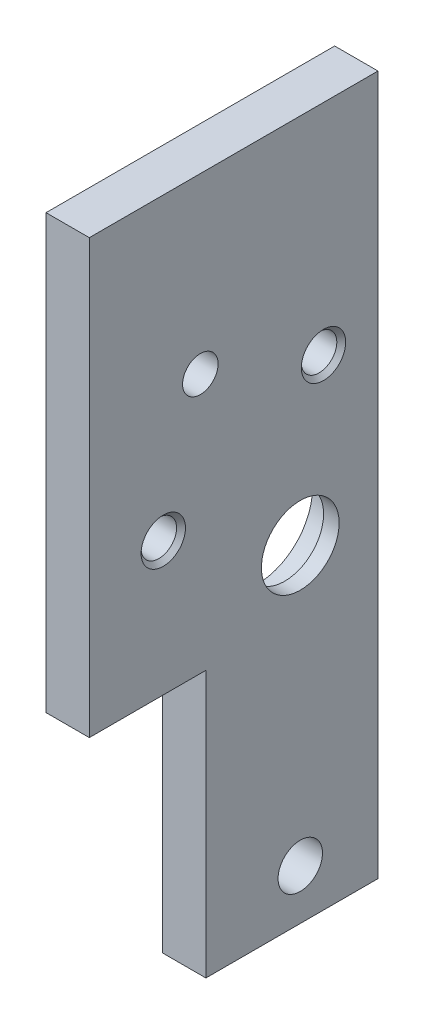
SolidWorks part; units mm, degrees
ref_plane "Front Plane" through (0, 0, 0) normal (0, 0, 1) x (1, 0, 0)
ref_plane "Top Plane" through (0, 0, 0) normal (0, 1, 0) x (1, 0, 0)
ref_plane "Right Plane" through (0, 0, 0) normal (1, 0, 0) x (0, 0, -1)
sketch "Sketch1" plane through (0, 0, 0) normal (1, 0, 0) x (0, 0, -1)
  line L1 (0, 0) -> (-30, 0)
  line L2 (0, 0) -> (0, 63)
  line L3 (0, 63) -> (-30, 63)
  line L4 (-30, 0) -> (-30, 63)
  dimension "D1" = 30
  dimension "D2" = 63
extrude "Boss-Extrude1" add sketch "Sketch1" against normal blind 3.9
sketch "Sketch2" plane through (0, 0, 0) normal (1, 0, 0) x (0, 0, -1)
  line L0 (-30, 0) -> (0, 0) construction
  line L1 (0, 0) -> (0, 63) construction
  circle A0 centre (-7, 29.5) radius 5
  dimension "D1" = 10
  dimension "D2" = 29.5
  dimension "D3" = 7
extrude "Cut-Extrude1" cut sketch "Sketch2" against normal through all
sketch "Sketch4" plane through (0, 0, 0) normal (1, 0, 0) x (0, 0, -1)
  line L0 (0, 0) -> (0, 63) construction
  line L1 (-15.3544, 41.2) -> (-2.5009, 48.379)
  line L2 (-2.5009, 48.379) -> (-15.1448, 55.921)
  line L3 (-15.1448, 55.921) -> (-15.3544, 41.2)
  circle A0 centre (-11, 48.5) radius 4.25 construction
  circle A1 centre (-7, 29.5) radius 5 construction
  dimension "D2" = 19
  dimension "D1" = 8.5
  dimension "D3" = 11
  dimension "D4" = 8.4991
hole_wizard "M4x0.7 Tapped Hole1" [suppressed] positions "3DSketch2" profile "Sketch6" tap size "M4x0.7" standard "ANSI Metric"
sketch3d "3DSketch2"
  point P0 (0, 38.7, 15.3544)
  point P3 (0, 45.879, 2.5009)
  point P6 (0, 53.421, 15.1448)
sketch "Sketch6" plane through (0, 38.7, 15.3544) normal (0, 1, 0) x (0, 0, -1)
  line L0 (0, 0) -> (0, 4)
  line L1 (0, 4) -> (1.05, 4)
  line L3 (1.05, 4) -> (1.05, 2)
  line L4 (1.05, 2) -> (1.65, 2)
  line L5 (1.65, 2) -> (1.65, 0)
  line L7 (1.65, 0) -> (0, 0)
  line L11 (0, -6.35) -> (0, 107.95) construction
  dimension "Thru Tap Drill Dia." = 2.1
  dimension "Thru Tap Drill Depth" = 4
  dimension "Thread Major Dia." = 3.3
  dimension "Thread Depth" = 2
sketch "Sketch7" [suppressed] plane through (-4, 0, 0) normal (-1, 0, 0) x (0, 0, 1)
  line L1 (15.3544, 38.7) -> (15.1448, 53.421)
  line L2 (15.1448, 53.421) -> (2.5009, 45.879)
  line L3 (2.5009, 45.879) -> (15.3544, 38.7)
  circle A0 centre (11, 46) radius 4.25 construction
hole_wizard "CBORE for M3 Pan Head Machine Screw1" [suppressed] positions "3DSketch3" profile "Sketch8" counterbore size "M3" standard "ANSI Metric"
sketch3d "3DSketch3" [suppressed]
  point P0 (-4, 46, 11)
sketch "Sketch8" [suppressed] plane through (-4, 46, 11) normal (0, 1, 0) x (0, 0, 1)
  line L0 (0, 0) -> (0, 4)
  line L1 (0, 4) -> (1.6, 4)
  line L3 (1.6, 4) -> (1.6, 1)
  line L4 (1.6, 1) -> (5.1, 1)
  line L5 (5.1, 1) -> (5.1, 0)
  line L7 (5.1, 0) -> (0, 0)
  line L11 (0, -6.35) -> (0, 107.95) construction
  dimension "Thru Hole Dia." = 3.2
  dimension "Thru Hole Depth" = 4
  dimension "C'Bore Dia." = 10.2
  dimension "C'Bore Depth" = 1
sketch "Sketch10" plane through (0, 0, 0) normal (1, 0, 0) x (0, 0, -1)
  line L0 (0, 0) -> (0, 63) construction
  line L1 (-30, 0) -> (0, 0) construction
  circle A0 centre (-7, 4.5) radius 2
  dimension "D1" = 4
  dimension "D2" = 7
  dimension "D3" = 4.5
hole_wizard "Ø4.0 (4) Diameter Hole1" positions "3DSketch4" profile "Sketch11" hole size "Ø4.0" standard "ANSI Metric" end condition through all
sketch3d "3DSketch4"
  point P0 (0, 4.5, 7)
sketch "Sketch11" plane through (0, 4.5, 7) normal (0, 1, 0) x (0, 0, -1)
  line L0 (0, 0) -> (0, 3.9)
  line L1 (0, 3.9) -> (2, 3.9)
  line L2 (2, 3.9) -> (2, 0)
  line L5 (2, 0) -> (0, 0)
  line L11 (0, -6.35) -> (0, 107.95) construction
  dimension "Thru Hole Dia." = 4
  dimension "Thru Hole Depth" = 3.9
sketch "Sketch12" plane through (0, 0, 0) normal (1, 0, 0) x (0, 0, -1)
  line L1 (-30, 0) -> (-15.5, 0)
  line L2 (-30, 0) -> (-30, 24)
  line L3 (-30, 24) -> (-15.5, 24)
  line L4 (-15.5, 0) -> (-15.5, 24)
  dimension "D1" = 14.5
  dimension "D2" = 24
extrude "Cut-Extrude2" cut sketch "Sketch12" against normal through all
sketch "Sketch13" plane through (-3.9, 0, 0) normal (-1, 0, 0) x (0, 0, 1)
  line L0 (0, 0) -> (0, 63) construction
  circle A0 centre (16, 47.3606) radius 1.5
  circle A1 centre (7, 29.5) radius 5 construction
  dimension "D1" = 3
  dimension "D2" = 20
  dimension "D3" = 16
hole_wizard "CBORE for M3 Pan Head Machine Screw2" positions "3DSketch5" profile "Sketch14" counterbore size "M3" standard "ANSI Metric" end condition through all
sketch3d "3DSketch5"
  point P0 (-3.9, 47.3606, 16)
sketch "Sketch14" plane through (-3.9, 47.3606, 16) normal (0, 1, 0) x (0, 0, 1)
  line L0 (0, 0) -> (0, 3.9)
  line L1 (0, 3.9) -> (1.6, 3.9)
  line L3 (1.6, 3.9) -> (1.6, 1)
  line L4 (1.6, 1) -> (4.5, 1)
  line L5 (4.5, 1) -> (4.5, 0)
  line L7 (4.5, 0) -> (0, 0)
  line L11 (0, -6.35) -> (0, 107.95) construction
  dimension "Thru Hole Dia." = 3.2
  dimension "Thru Hole Depth" = 3.9
  dimension "C'Bore Dia." = 9
  dimension "C'Bore Depth" = 1
sketch "Sketch16" plane through (0, 0, 0) normal (1, 0, 0) x (0, 0, -1)
  line L0 (-16, 47.3606) -> (-7, 29.5) construction
  circle A0 centre (-19.3397, 36.0326) radius 1.5
  circle A1 centre (-16, 47.3606) radius 1.6 construction
  circle A2 centre (-4.9083, 43.3046) radius 1.5
  dimension "D1" = 3
  dimension "D2" = 8.08
  dimension "D3" = 11.81
hole_wizard "CSK for M3 Flat Head Machine Screw1" positions "3DSketch7" profile "Sketch18" countersink size "M3" standard "ANSI Metric" end condition through all
sketch3d "3DSketch7"
  point P0 (0, 36.0326, 19.3397)
  point P3 (0, 43.3046, 4.9083)
sketch "Sketch18" plane through (0, 36.0326, 19.3397) normal (0, 1, 0) x (0, 0, -1)
  line L0 (0, 0) -> (0, 3.9)
  line L1 (0, 3.9) -> (1.6, 3.9)
  line L2 (1.6, 3.9) -> (1.6, 0.4)
  line L3 (1.6, 0.4) -> (2, 0)
  line L5 (2, 0) -> (0, 0)
  line L6 (-1.6, 0.4) -> (-2, 0) construction
  line L11 (0, -6.35) -> (0, 107.95) construction
  dimension "Thru Hole Dia." = 3.2
  dimension "Thru Hole Depth" = 3.9
  dimension "Near C'Sink Dia." = 4
  dimension "Near C'Sink Angle" = 90
sketch "Sketch19" plane through (-3.9, 0, 0) normal (-1, 0, 0) x (0, 0, 1)
  line L0 (30, 24) -> (30, 63)
  line L1 (30, 24) -> (26, 24)
  line L2 (30, 63) -> (26, 63)
  line L3 (26, 24) -> (26, 63)
  dimension "D1" = 4
extrude "Cut-Extrude3" cut sketch "Sketch19" against normal through all
sketch "Sketch20" plane through (0, 0, 0) normal (1, 0, 0) x (0, 0, -1)
  circle A0 centre (-7, 29.5) radius 5
  circle A1 centre (-7, 29.5) radius 3.5
  dimension "D1" = 10
  dimension "D2" = 7
extrude "Boss-Extrude2" add sketch "Sketch20" against normal blind 1.4
